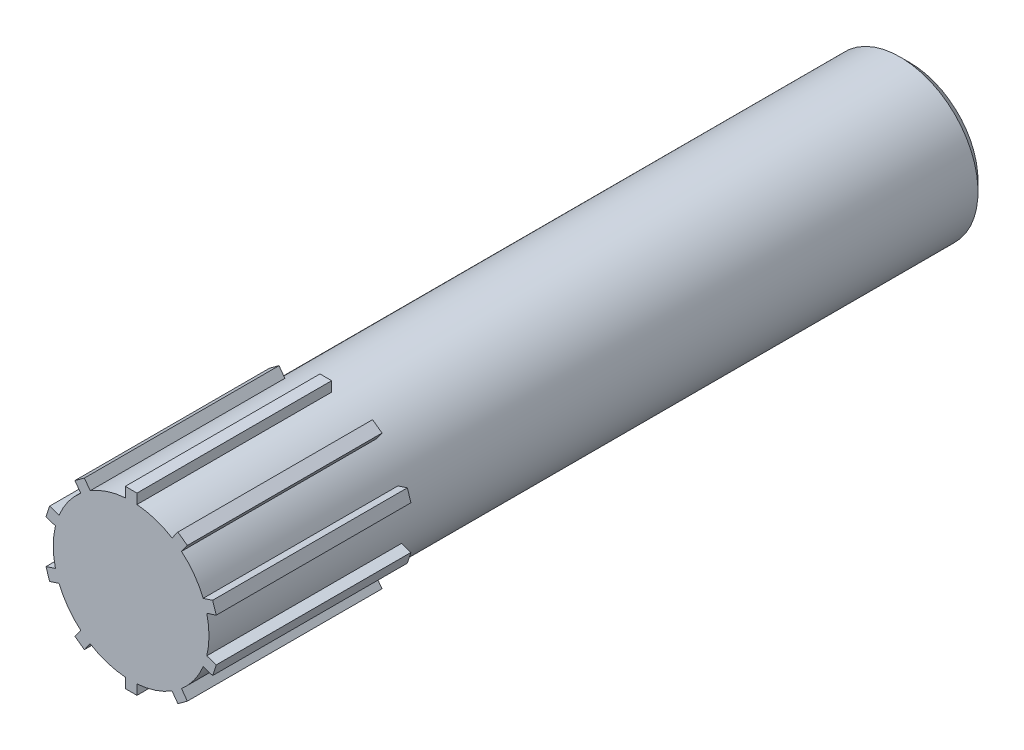
SolidWorks part; units mm, degrees
ref_plane "Front Plane" through (0, 0, 0) normal (0, 0, 1) x (1, 0, 0)
ref_plane "Top Plane" through (0, 0, 0) normal (0, 1, 0) x (1, 0, 0)
ref_plane "Right Plane" through (0, 0, 0) normal (1, 0, 0) x (0, 0, -1)
sketch "Sketch2" plane through (0, 0, 0) normal (0, 0, 1) x (1, 0, 0)
  circle A0 centre (0, 0) radius 4
  dimension "D1" = 8
extrude "Boss-Extrude1" add sketch "Sketch2" along normal blind 40
sketch "Sketch3" plane through (0, 0, 0) normal (0, 1, 0) x (1, 0, 0)
  line L0 (0, 0) -> (0, -4) construction
  line L1 (1.5, 0) -> (1.5, -4)
  line L2 (-1.5, 0) -> (-1.5, -4)
  arc A0 (1.5, 0) -> (-1.5, 0) centre (0, 0) ccw
  arc A1 (-1.5, -4) -> (1.5, -4) centre (0, -4) ccw
  point P3 (0, -2)
  dimension "D1" = 1.5
  dimension "D2" = 4
extrude "Cut-Extrude3" cut sketch "Sketch3" against normal through all from offset 2.5 offset against normal yes
chamfer "Chamfer1" distance 0.5 angle 45 1 edges at (0, 4, 0)
sketch "Sketch4" plane through (0, 0, 40) normal (0, 0, 1) x (1, 0, 0)
  line L0 (0, 0) -> (0, 4) construction
  line L2 (0.3, 3.5) -> (-0.3, 3.5)
  line L3 (0.3, 3.5) -> (0.3, 4.5)
  line L4 (0.3, 4.5) -> (-0.3, 4.5)
  line L5 (-0.3, 3.5) -> (-0.3, 4.5)
  line L6 (0.3, 3.5) -> (-0.3, 4.5) construction
  line L7 (0.3, 4.5) -> (-0.3, 3.5) construction
  circle A0 centre (0, 0) radius 4 construction
  dimension "D1" = 0.6
  dimension "D2" = 4.5
extrude "Boss-Extrude2" add sketch "Sketch4" against normal blind 10
pattern_circular "CirPattern1" count 10 over 360 about axis through (0, 0, 0) along (0, 0, 1) of "Boss-Extrude2"
